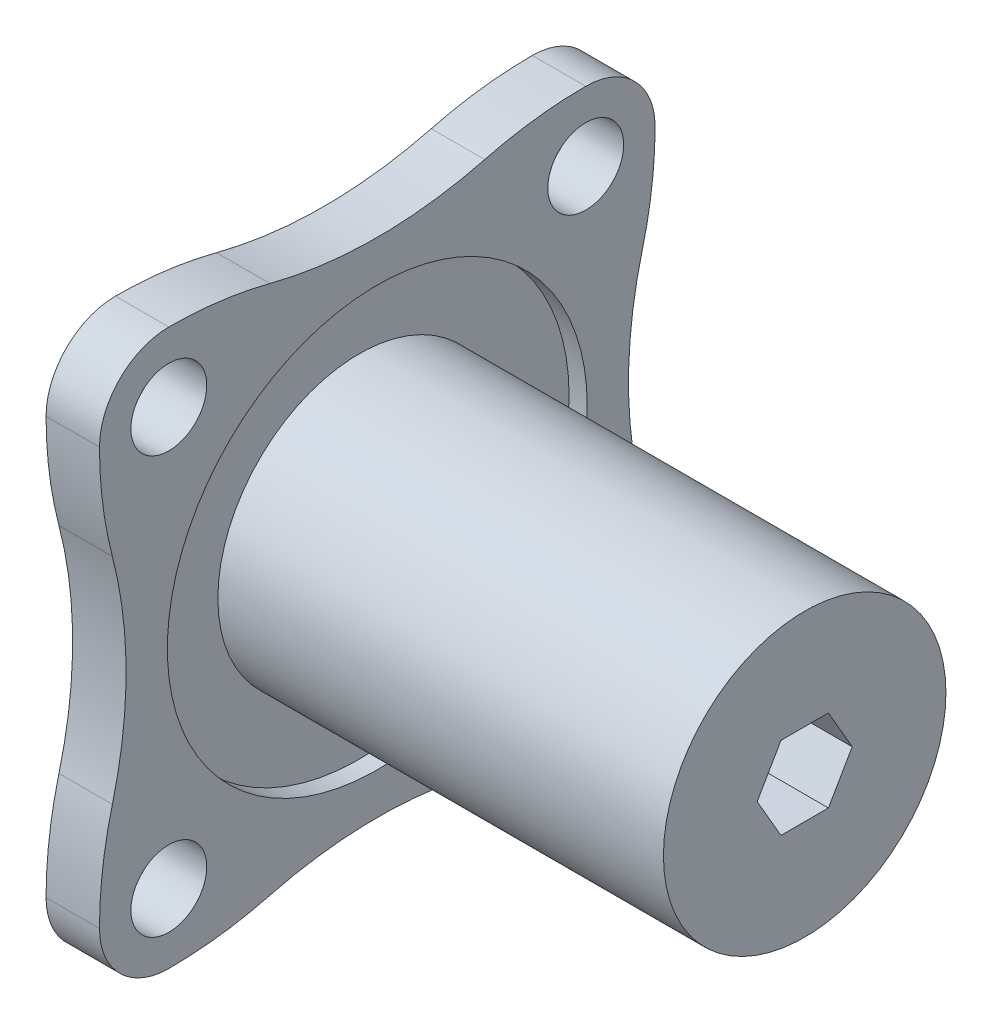
SolidWorks part; units mm, degrees
material "ABS"
ref_plane "Front Plane" through (0, 0, 0) normal (0, 0, 1) x (1, 0, 0)
ref_plane "Top Plane" through (0, 0, 0) normal (0, 1, 0) x (1, 0, 0)
ref_plane "Right Plane" through (0, 0, 0) normal (1, 0, 0) x (0, 0, -1)
sketch "Sketch1" plane through (0, 0, 0) normal (1, 0, 0) x (0, 0, -1)
  line L1 (-2.823, -4.8895) -> (2.823, -4.8895)
  line L2 (2.823, -4.8895) -> (5.6459, 0)
  line L3 (5.6459, 0) -> (2.823, 4.8895)
  line L4 (2.823, 4.8895) -> (-2.823, 4.8895)
  line L5 (-2.823, 4.8895) -> (-5.6459, 0)
  line L6 (-5.6459, 0) -> (-2.823, -4.8895)
  circle A0 centre (0, 0) radius 16.7894
  circle A1 centre (0, 0) radius 4.8895 construction
  dimension "D1" = 9.779
  dimension "D2" = 33.5788
extrude "Boss-Extrude1" add sketch "Sketch1" along normal blind 50.8
sketch "Sketch2" plane through (0, 0, 0) normal (-1, 0, 0) x (0, 0, 1)
  line L0 (0, -31.4325) -> (0, 31.4325) construction
  line L1 (-33.02, -33.02) -> (33.02, -33.02) construction
  line L2 (-33.02, -33.02) -> (-33.02, 33.02) construction
  line L3 (-33.02, 33.02) -> (33.02, 33.02) construction
  line L4 (33.02, -33.02) -> (33.02, 33.02) construction
  line L5 (-33.02, -33.02) -> (33.02, 33.02) construction
  line L6 (-33.02, 33.02) -> (33.02, -33.02) construction
  line L7 (-24.7777, -24.7777) -> (24.7777, -24.7777) construction
  line L8 (-24.7777, -24.7777) -> (-24.7777, 24.7777) construction
  line L9 (-24.7777, 24.7777) -> (24.7777, 24.7777) construction
  line L10 (24.7777, -24.7777) -> (24.7777, 24.7777) construction
  line L11 (-24.7777, -24.7777) -> (24.7777, 24.7777) construction
  line L12 (-24.7777, 24.7777) -> (24.7777, -24.7777) construction
  line L13 (2.823, 4.8895) -> (-2.823, 4.8895)
  line L14 (-2.823, 4.8895) -> (-5.6459, 0)
  line L15 (-5.6459, 0) -> (-2.823, -4.8895)
  line L16 (-2.823, -4.8895) -> (2.823, -4.8895)
  line L17 (2.823, -4.8895) -> (5.6459, 0)
  line L18 (5.6459, 0) -> (2.823, 4.8895)
  line L19 (31.4325, 0) -> (-31.4325, 0) construction
  circle A0 centre (24.7777, 24.7777) radius 4.5085
  circle A1 centre (-24.7777, 24.7777) radius 4.5085
  circle A2 centre (-24.7777, -24.7777) radius 4.5085
  circle A3 centre (24.7777, -24.7777) radius 4.5085
  circle A4 centre (0, 0) radius 4.8895 construction
  arc A5 (-24.7777, 33.02) -> (-33.02, 24.7777) centre (-24.7777, 24.7777) ccw
  arc A6 (-31.4861, 12.7591) -> (-31.4861, -12.7591) centre (-80.6577, 0) cw
  arc A7 (-31.4861, 12.7591) -> (-33.02, 24.7777) centre (14.832, 24.7777) cw
  arc A8 (-31.4861, -12.7591) -> (-33.02, -24.7777) centre (14.832, -24.7777) ccw
  arc A9 (-33.02, -24.7777) -> (-24.7777, -33.02) centre (-24.7777, -24.7777) ccw
  arc A10 (-24.7777, 33.02) -> (-12.7591, 31.4861) centre (-24.7777, -14.832) cw
  arc A11 (-12.7591, 31.4861) -> (12.7591, 31.4861) centre (0, 80.6577) ccw
  arc A12 (12.7591, 31.4861) -> (24.7777, 33.02) centre (24.7777, -14.832) cw
  arc A13 (33.02, -24.7777) -> (24.7777, -33.02) centre (24.7777, -24.7777) cw
  arc A14 (31.4861, -12.7591) -> (33.02, -24.7777) centre (-14.832, -24.7777) cw
  arc A15 (31.4861, 12.7591) -> (31.4861, -12.7591) centre (80.6577, 0) ccw
  arc A16 (31.4861, 12.7591) -> (33.02, 24.7777) centre (-14.832, 24.7777) ccw
  arc A17 (24.7777, 33.02) -> (33.02, 24.7777) centre (24.7777, 24.7777) cw
  arc A18 (12.7591, -31.4861) -> (24.7777, -33.02) centre (24.7777, 14.832) ccw
  arc A19 (-12.7591, -31.4861) -> (12.7591, -31.4861) centre (0, -80.6577) cw
  arc A20 (-24.7777, -33.02) -> (-12.7591, -31.4861) centre (-24.7777, 14.832) ccw
  circle A21 centre (0, 0) radius 24.9555 construction
  point P0 (0, 0)
  point P6 (0, 0)
  dimension "D2" = 9.017
  dimension "D4" = 5.08
  dimension "D5" = 49.911
  dimension "D6" = 50.8
  dimension "D1" = 40.5384
  dimension "D3" = 66.04
extrude "Boss-Extrude2" add sketch "Sketch2" along normal blind 6.35
sketch "Sketch3" plane through (0, 0, 0) normal (1, 0, 0) x (0, 0, -1)
  circle A0 centre (0, 0) radius 24.9555
  circle A1 centre (0, 0) radius 16.7894
  circle A2 centre (0, 0) radius 16.7894 construction
  dimension "D1" = 49.911
extrude "Cut-Extrude1" cut sketch "Sketch3" against normal blind 2.159
